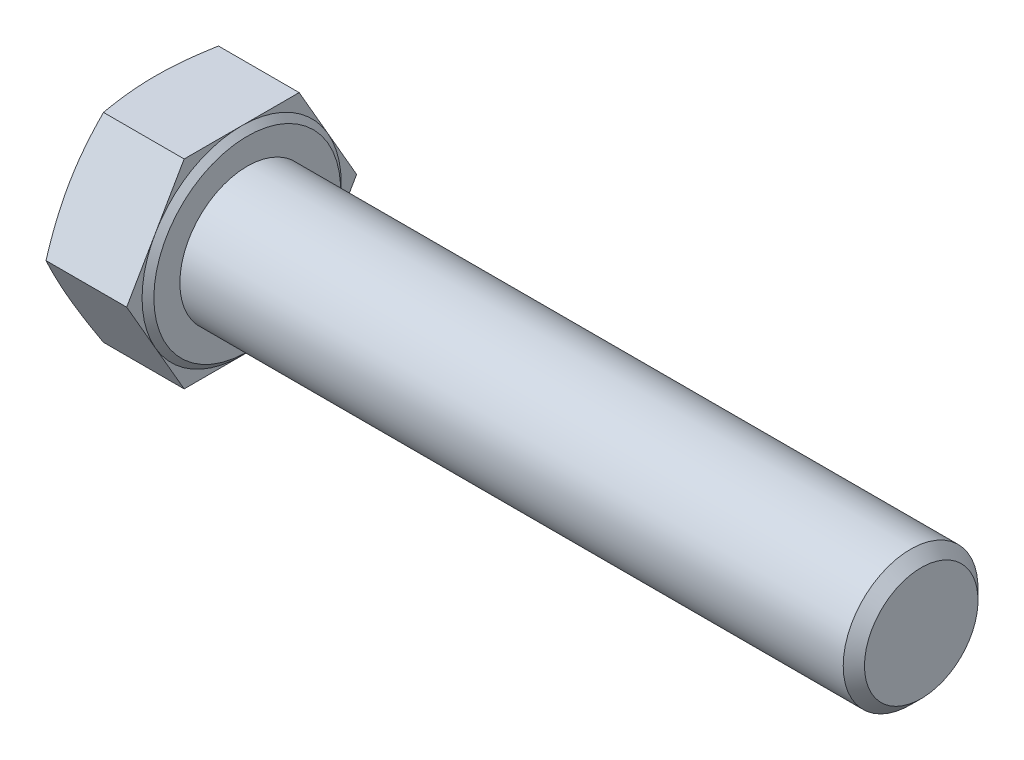
SolidWorks part; units mm, degrees
ref_plane "Front" through (0, 0, 0) normal (0, 0, 1) x (1, 0, 0)
ref_plane "Top" through (0, 0, 0) normal (0, 1, 0) x (1, 0, 0)
ref_plane "Right" through (0, 0, 0) normal (1, 0, 0) x (0, 0, -1)
other "Configuration Table"
sketch "Sketch-BaseHead" plane through (0, 0, 0) normal (1, 0, 0) x (0, 0, -1)
  line L1 (10.2364, 0) -> (5.1182, 8.865)
  line L2 (5.1182, 8.865) -> (-5.1182, 8.865)
  line L3 (-5.1182, 8.865) -> (-10.2364, 0)
  line L4 (-10.2364, 0) -> (-5.1182, -8.865)
  line L5 (-5.1182, -8.865) -> (5.1182, -8.865)
  line L6 (5.1182, -8.865) -> (10.2364, 0)
  circle A0 centre (0, 0) radius 8.865 construction
  dimension "s" = 17.73
extrude "BaseHead" add sketch "Sketch-BaseHead" along normal blind 7.68
sketch "Sketch4" plane through (-0.2646, 0, 5.9169) normal (0, 1, 0) x (0, 0, -1)
  line L0 (5.9169, 3.7369) -> (5.9169, -10.4477) construction
  line L2 (16.1533, -0.2646) -> (14.7819, -0.2646)
  line L4 (14.7819, -0.2646) -> (16.1533, -0.7638)
  line L6 (16.1533, -0.7638) -> (16.1533, -0.2646)
  dimension "D1" = 20
  dimension "D2" = 17.73
revolve "HeadChamfer" cut sketch "Sketch4" angle 360 about L0
sketch "Sketch1" plane through (0, 0, 0) normal (0, 0, 1) x (1, 0, 0)
  line L0 (7.68, 0) -> (8.18, 0)
  line L1 (8.18, 0) -> (8.18, -8.315)
  line L2 (8.18, -8.315) -> (7.68, -8.865)
  line L3 (7.68, -8.865) -> (7.68, 0) construction
  line L4 (0, 0) -> (7.5821, 0) construction
  line L5 (-4.0016, 0) -> (10.1831, 0) construction
  line L6 (7.68, -8.865) -> (0.4992, -8.865) construction
  line L7 (7.68, 0) -> (7.68, -8.865)
  dimension "c" = 0.5
  dimension "D1" = 8.865
  dimension "D2" = 8.315
revolve "Revolve1" add sketch "Sketch1" angle 360 about axis through (-4.0016, 0, 0) along (1, 0, 0)
ref_plane "Plane2" through (38.18, 0, 0) normal (1, 0, 0) x (0, 0, -1)
sketch "Sketch3" plane through (8.18, 0, 0) normal (1, 0, 0) x (0, 0, -1)
  circle A0 centre (0, 0) radius 6
  dimension "d" = 12
extrude "BaseBody" add sketch "Sketch3" along normal blind 60
cosmetic thread "ThreadCosmetic1" [suppressed] parameters "b"=30, "D2"=10.106
fillet "HeadFillet" [suppressed] radius 0.6
chamfer "Chamfer1" distance 0.947 angle 45 1 edges at (68.18, 0, -6)
sketch "Sketch5" plane through (0, 0, 0) normal (0, 0, 1) x (1, 0, 0)
  line L0 (66.286, 6.947) -> (67.233, 6.947)
  line L1 (67.233, 6.947) -> (67.233, 6)
  line L2 (67.233, 6) -> (66.7595, 5.1799)
  line L3 (66.7595, 5.1799) -> (66.286, 6)
  line L4 (66.286, 6) -> (66.286, 6.947)
  line L5 (67.233, -6) -> (67.233, 6) construction
  line L6 (67.233, 6) -> (8.18, 6) construction
  dimension "D1" = 0.947
revolve "Cut-Revolve10" [suppressed] cut sketch "Sketch5" angle 360
pattern_linear "LPattern10" [suppressed] count 26
equation "\"D1@Sketch1\" = \"s@Sketch-BaseHead\"/ 2"
equation "\"D2@Sketch4\" = \"s@Sketch-BaseHead\""
equation "\"D1@Chamfer1\" =  ( \"d@Sketch3\" - \"D2@ThreadCosmetic1\" ) / 2 "
equation "\"b@ThreadCosmetic1\" = \"l@BaseBody\" - \"lg@Plane2\""
equation "\"D1@Sketch5\" =  (\"d@Sketch3\" - \"D2@ThreadCosmetic1\" )  / 2 "
equation "\"pitch@LPattern10\" = 1.2 * \"D1@Sketch5\""
equation "\"D1@LPattern10\" = \"b@ThreadCosmetic1\" / \"pitch@LPattern10\""
